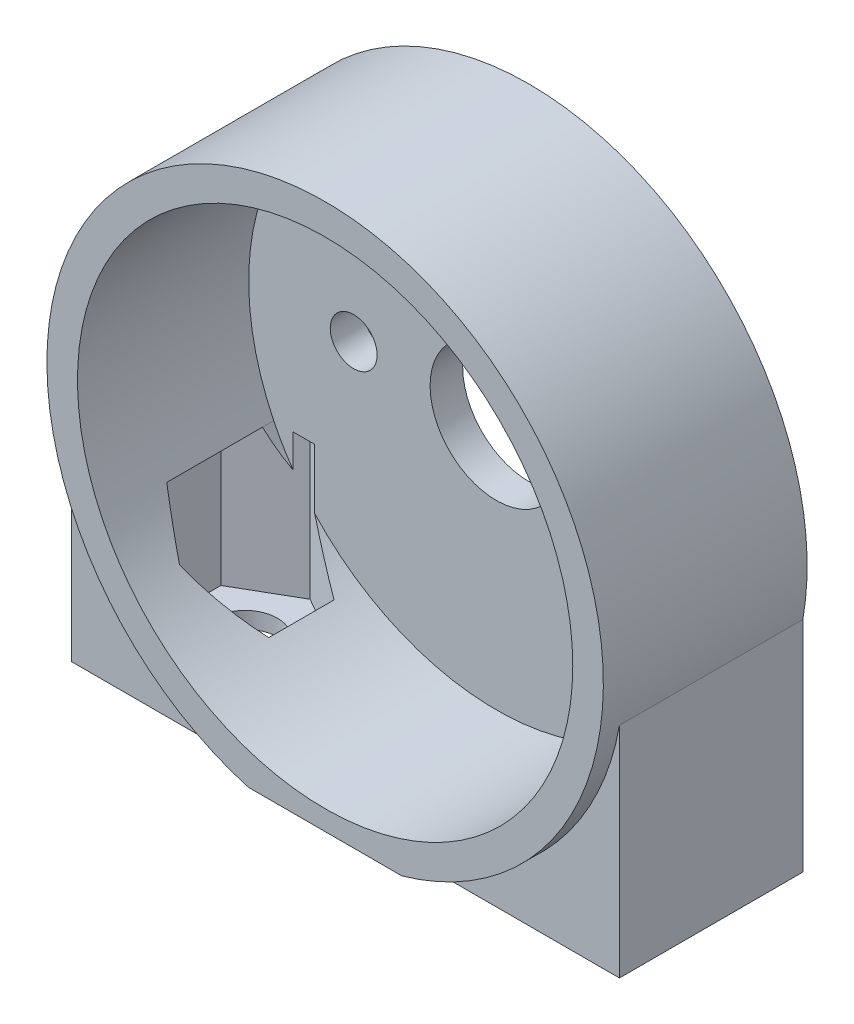
SolidWorks part; units mm, degrees
ref_plane "Front Plane" through (0, 0, 0) normal (0, 0, 1) x (1, 0, 0)
ref_plane "Top Plane" through (0, 0, 0) normal (0, 1, 0) x (1, 0, 0)
ref_plane "Right Plane" through (0, 0, 0) normal (1, 0, 0) x (0, 0, -1)
sketch "Sketch1" plane through (0, 0, 0) normal (0, 0, 1) x (1, 0, 0)
  circle A0 centre (0, 0) radius 12.15
  circle A1 centre (0, 0) radius 13.65
extrude "Boss-Extrude1" add sketch "Sketch1" along normal blind 10
sketch "Sketch2" plane through (0, 0, 10) normal (0, 0, 1) x (1, 0, 0)
  line L0 (5.5, 0) -> (-5.5, 0) construction
  line L1 (-9.25, 0) -> (9.25, 0) construction
  line L2 (0, -5.5) -> (0, 5.5) construction
  circle A0 centre (0, 0) radius 13.65
  circle A1 centre (0, 0) radius 4.25
  circle A2 centre (9.25, 0) radius 1.5
  circle A3 centre (-9.25, 0) radius 1.5
  point P10 (0, 0)
  dimension "D1" = 18.5
  dimension "D2" = 8.5
  dimension "D3" = 3
sketch "Sketch3" plane through (0, 0, 0) normal (0, 0, -1) x (-1, 0, 0)
  line L0 (-9.44, -13.65) -> (9.44, -13.65) construction
  line L2 (0, 5.5) -> (0, -5.5) construction
  line L4 (-13.44, -2.3851) -> (-13.44, -13.65)
  line L5 (-13.44, -13.65) -> (13.44, -13.65)
  line L6 (13.44, -2.3851) -> (13.44, -13.65)
  circle A1 centre (0, 0) radius 13.65 construction
  circle A3 centre (0, 0) radius 13.65
  point P2 (0, -13.65)
  point P5 (0, 0)
  point P13 (0, -13.65)
  point P14 (0, 0)
  dimension "D1" = 18.88
  dimension "D2" = 4
extrude "Boss-Extrude3" add sketch "Sketch3" against normal blind 9
sketch "Sketch5" plane through (0, -13.65, 0) normal (0, -1, 0) x (1, 0, 0)
  line L1 (-9.44, 4.5) -> (9.44, 4.5) construction
  line L2 (-9.44, 0) -> (-9.44, 9) construction
  line L3 (15.015, 0) -> (-15.015, 0) construction
  line L4 (0, 9) -> (-13.44, 9) construction
  line L5 (0, -5.5) -> (0, 5.5) construction
  circle A0 centre (-9.44, 4.5) radius 1.6
  circle A2 centre (9.44, 4.5) radius 1.6
  point P4 (0, 4.5)
  point P14 (-9.44, 4.5)
  dimension "D1" = 18.88
  dimension "D3" = 3.2
extrude "Cut-Extrude1" cut sketch "Sketch5" against normal blind 7
sketch "Sketch6" plane through (0, 0, 0) normal (0, 0, -1) x (-1, 0, 0)
  line L1 (-13.44, -13.65) -> (13.44, -13.65)
  line L2 (-13.44, -13.65) -> (-13.44, -13.12)
  line L3 (-13.44, -13.12) -> (13.44, -13.12)
  line L4 (13.44, -13.65) -> (13.44, -13.12)
  line L6 (13.44, -2.3851) -> (13.44, -13.65) construction
  dimension "D1" = 0.53
extrude "Cut-Extrude2" cut sketch "Sketch6" against normal through all
sketch "Sketch7" plane through (0, 0, 0) normal (0, 0, -1) x (-1, 0, 0)
  line L0 (9.25, 0) -> (-9.25, 0) construction
  line L1 (-7, 0) -> (7, 0) construction
  line L2 (0, 5.5) -> (0, -5.5) construction
  circle A0 centre (0, 0) radius 12.15
  circle A1 centre (-7, 0) radius 1.15
  circle A2 centre (7, 0) radius 1.15
  circle A3 centre (0, 0) radius 3.25
  point P6 (0, 0)
  dimension "D1" = 14
  dimension "D2" = 2.3
  dimension "D3" = 2.3
  dimension "D4" = 6.5
extrude "Boss-Extrude4" add sketch "Sketch7" against normal blind 1.6
sketch "Sketch8" plane through (0, -13.12, 0) normal (0, -1, 0) x (1, 0, 0)
  line L0 (-13.44, 9) -> (-13.44, 0) construction
  line L1 (-12.215, 2.8979) -> (-9.44, 1.2957)
  line L2 (-9.44, 1.2957) -> (-6.665, 2.8979)
  line L3 (-6.665, 2.8979) -> (-6.665, 6.1021)
  line L4 (-6.665, 6.1021) -> (-9.44, 7.7043)
  line L5 (-9.44, 7.7043) -> (-12.215, 6.1021)
  line L6 (-12.215, 6.1021) -> (-12.215, 2.8979)
  line L7 (0, -5.5) -> (0, 5.5) construction
  line L8 (12.215, 6.1021) -> (12.215, 2.8979)
  line L9 (9.44, 7.7043) -> (12.215, 6.1021)
  line L10 (6.665, 6.1021) -> (9.44, 7.7043)
  line L11 (6.665, 2.8979) -> (6.665, 6.1021)
  line L12 (9.44, 1.2957) -> (6.665, 2.8979)
  line L13 (12.215, 2.8979) -> (9.44, 1.2957)
  circle A0 centre (-9.44, 4.5) radius 2.775 construction
  dimension "D1" = 5.55
extrude "Cut-Extrude4" cut sketch "Sketch8" against normal blind 7 from offset 0.8 offset against normal yes
